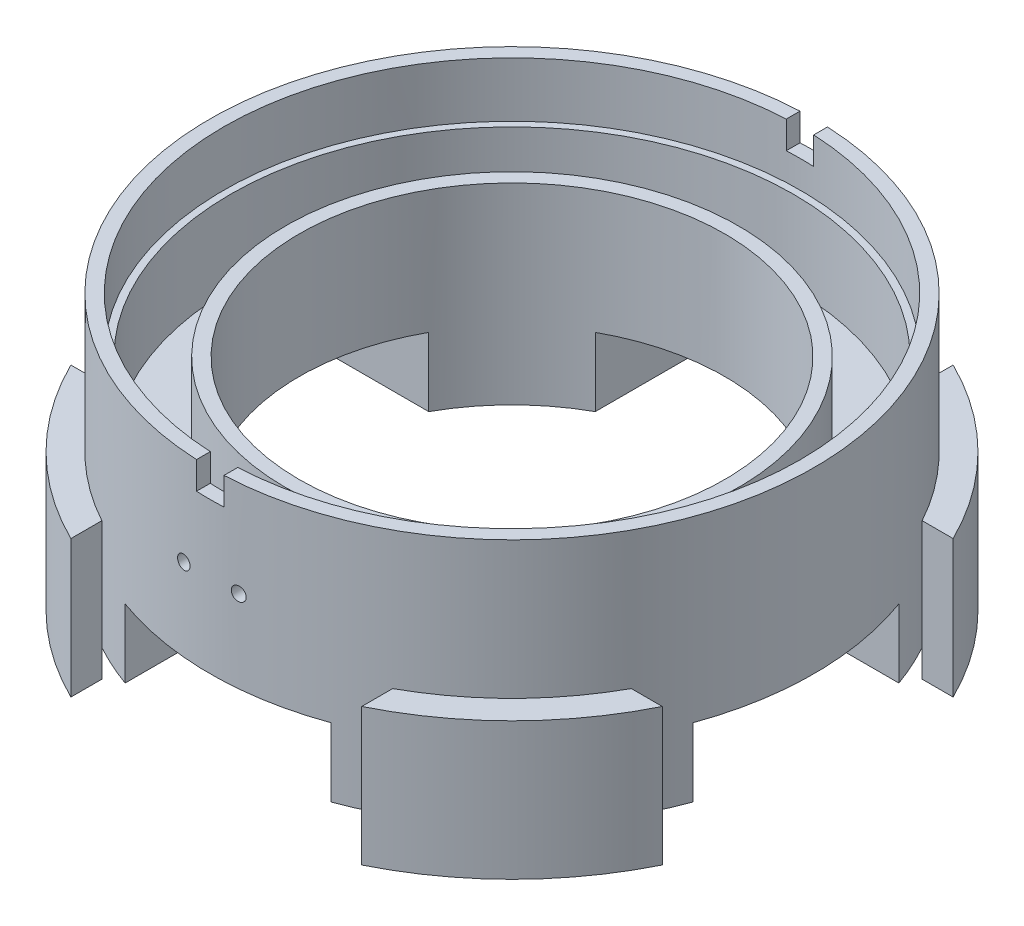
SolidWorks part; units mm, degrees
ref_plane "前视基准面" through (0, 0, 0) normal (0, 0, 1) x (1, 0, 0)
ref_plane "上视基准面" through (0, 0, 0) normal (0, 1, 0) x (1, 0, 0)
ref_plane "右视基准面" through (0, 0, 0) normal (1, 0, 0) x (0, 0, -1)
other "Configuration Table"
sketch "草图1" plane through (0, 0, 0) normal (0, 1, 0) x (1, 0, 0)
  line L16 (-10.5917, 21.5364) -> (-10.5917, 19.2825)
  line L17 (10.5917, 21.5364) -> (10.5917, 19.2825)
  line L18 (-21.5364, 10.5917) -> (-19.2825, 10.5917)
  line L19 (21.5364, 10.5917) -> (19.2825, 10.5917)
  line L20 (-21.5364, -10.5917) -> (-19.2825, -10.5917)
  line L21 (-10.5917, -21.5364) -> (-10.5917, -19.2825)
  line L22 (21.5364, -10.5917) -> (19.2825, -10.5917)
  line L23 (10.5917, -21.5364) -> (10.5917, -19.2825)
  arc A16 (-10.5917, 19.2825) -> (-19.2825, 10.5917) centre (0, 0) ccw
  arc A17 (-10.5917, 21.5364) -> (-21.5364, 10.5917) centre (0, 0) ccw
  arc A18 (19.2825, 10.5917) -> (10.5917, 19.2825) centre (0, 0) ccw
  arc A19 (21.5364, 10.5917) -> (10.5917, 21.5364) centre (0, 0) ccw
  arc A20 (10.5917, -19.2825) -> (19.2825, -10.5917) centre (0, 0) ccw
  arc A21 (10.5917, -21.5364) -> (21.5364, -10.5917) centre (0, 0) ccw
  arc A22 (-19.2825, -10.5917) -> (-10.5917, -19.2825) centre (0, 0) ccw
  arc A23 (-21.5364, -10.5917) -> (-10.5917, -21.5364) centre (0, 0) ccw
extrude "凸台-拉伸1" add sketch "草图1" along normal blind 2
sketch "草图4" plane through (0, 2, 0) normal (0, 1, 0) x (1, 0, 0)
  line L0 (-10.5917, 21.5364) -> (-10.5917, 19.2825)
  line L1 (10.5917, 21.5364) -> (10.5917, 19.2825)
  line L2 (-21.5364, 10.5917) -> (-19.2825, 10.5917)
  line L3 (21.5364, 10.5917) -> (19.2825, 10.5917)
  line L4 (-21.5364, -10.5917) -> (-19.2825, -10.5917)
  line L5 (-10.5917, -21.5364) -> (-10.5917, -19.2825)
  line L6 (21.5364, -10.5917) -> (19.2825, -10.5917)
  line L7 (10.5917, -21.5364) -> (10.5917, -19.2825)
  arc A1 (-10.5917, 21.5364) -> (-21.5364, 10.5917) centre (0, 0) ccw
  arc A3 (21.5364, 10.5917) -> (10.5917, 21.5364) centre (0, 0) ccw
  arc A5 (10.5917, -21.5364) -> (21.5364, -10.5917) centre (0, 0) ccw
  arc A7 (-21.5364, -10.5917) -> (-10.5917, -21.5364) centre (0, 0) ccw
  arc A8 (-19.2825, 10.5917) -> (-19.2825, -10.5917) centre (0, 0) ccw
  arc A9 (-10.5917, -19.2825) -> (10.5917, -19.2825) centre (0, 0) ccw
  arc A10 (19.2825, -10.5917) -> (19.2825, 10.5917) centre (0, 0) ccw
  arc A11 (10.5917, 19.2825) -> (-10.5917, 19.2825) centre (0, 0) ccw
extrude "凸台-拉伸2" add sketch "草图4" along normal blind 8
sketch "草图5" plane through (0, 10, 0) normal (0, 1, 0) x (1, 0, 0)
  circle A0 centre (0, 0) radius 22
  circle A1 centre (0, 0) radius 20.5
extrude "凸台-拉伸3" add sketch "草图5" along normal blind 8
sketch "草图6" plane through (0, 10, 0) normal (0, 1, 0) x (1, 0, 0)
  circle A0 centre (0, 0) radius 15.5
  circle A1 centre (0, 0) radius 16.5
extrude "凸台-拉伸4" add sketch "草图6" along normal blind 7
sketch "草图7" plane through (0, 10, 0) normal (0, 1, 0) x (1, 0, 0)
  circle A0 centre (0, 0) radius 15.5
extrude "切除-拉伸1" cut sketch "草图7" against normal blind 10
sketch "草图8" plane through (0, 0, 0) normal (0, 0, 1) x (1, 0, 0)
  line L0 (0, 2) -> (0, 4.5) construction
  line L1 (-10.5917, 2) -> (10.5917, 2) construction
  line L3 (-7.5, 7) -> (7.5, 7)
  line L4 (-7.5, 7) -> (-7.5, 2)
  line L5 (-7.5, 2) -> (7.5, 2)
  line L6 (7.5, 7) -> (7.5, 2)
  line L7 (-7.5, 7) -> (7.5, 2) construction
  line L8 (-7.5, 2) -> (7.5, 7) construction
extrude "切除-拉伸2" cut sketch "草图8" against normal through all both and the other way through all
pattern_circular "阵列(圆周)1" count 2 every 90 about axis through (0, 10, 0) along (0, -1, 0) of "切除-拉伸2"
sketch "草图9" plane through (0, 18, 0) normal (0, 1, 0) x (1, 0, 0)
  line L4 (0, 0) -> (10.2642, 0) construction
  line L5 (1, -20.9762) -> (1, -21.9773)
  line L6 (1, 20.9762) -> (1, 21.9773)
  line L7 (-1, 20.9762) -> (-1, 21.9773)
  line L8 (-1, -20.9762) -> (-1, -21.9773)
  arc A8 (-1, 20.9762) -> (-1, -20.9762) centre (0, 0) ccw
  arc A9 (1, -21.9773) -> (1, 21.9773) centre (0, 0) ccw
  arc A10 (1, -20.9762) -> (1, 20.9762) centre (0, 0) ccw
  arc A11 (-1, 21.9773) -> (-1, -21.9773) centre (0, 0) ccw
extrude "凸台-拉伸5" add sketch "草图9" along normal blind 2
sketch "草图10" plane through (0, 0, 0) normal (0, 0, 1) x (1, 0, 0)
  line L0 (0, 11) -> (0, 13) construction
  line L1 (0, 13) -> (-2, 13) construction
  circle A0 centre (-2, 13) radius 0.5
  circle A1 centre (2, 13) radius 0.5
extrude "切除-拉伸3" cut sketch "草图10" against normal blind 10 from offset 30
sketch "草图16" plane through (0, 18, 0) normal (0, 1, 0) x (1, 0, 0)
  circle A0 centre (0, 0) radius 21
extrude "切除-拉伸5" cut sketch "草图16" against normal blind 2
